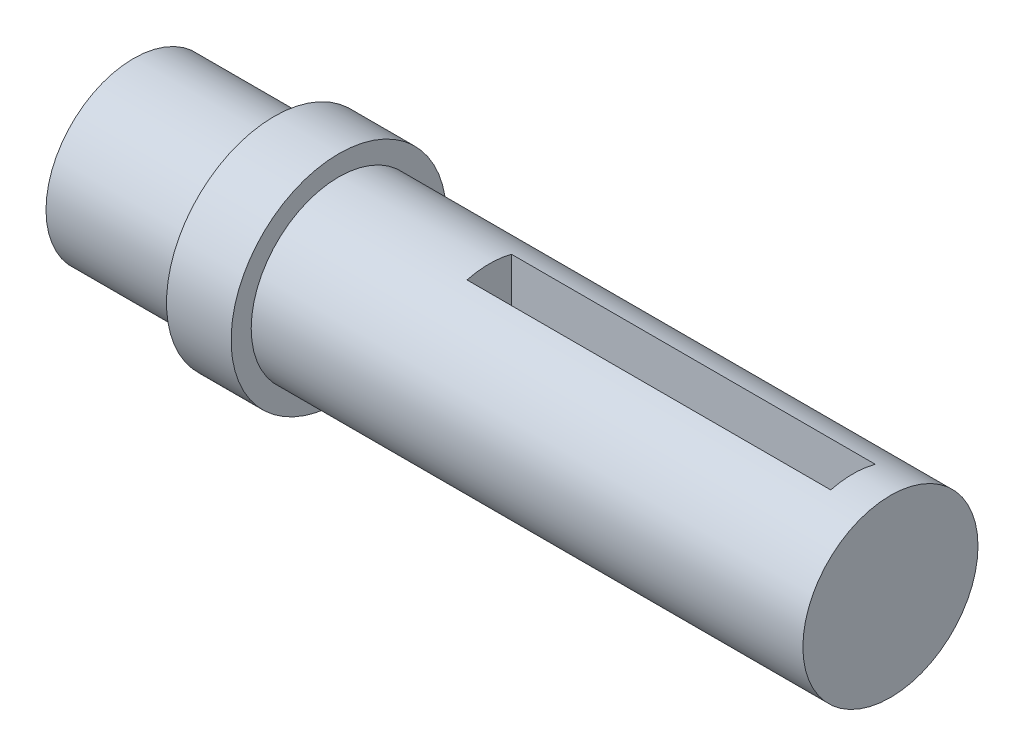
SolidWorks part; units mm, degrees
material "Plain Carbon Steel"
ref_plane "Front Plane" through (0, 0, 0) normal (0, 0, 1) x (1, 0, 0)
ref_plane "Top Plane" through (0, 0, 0) normal (0, 1, 0) x (1, 0, 0)
ref_plane "Right Plane" through (0, 0, 0) normal (1, 0, 0) x (0, 0, -1)
sketch "Sketch1" plane through (0, 0, 0) normal (0, 0, 1) x (1, 0, 0)
  line L0 (0, 0) -> (161.48, 0) construction
  line L1 (161.48, 0) -> (161.48, 18.68)
  line L2 (161.48, 18.68) -> (43.78, 18.68)
  line L3 (43.78, 18.68) -> (43.78, 22.97)
  line L4 (43.78, 22.97) -> (30, 22.97)
  line L5 (30, 22.97) -> (30, 18.68)
  line L6 (30, 18.68) -> (0, 18.68)
  line L7 (0, 18.68) -> (0, 0)
  line L8 (0, 0) -> (161.48, 0)
  dimension "D1" = 16.38
  dimension "D2" = 22.97
  dimension "D3" = 16.38
  dimension "D4" = 117.7
  dimension "D5" = 13.78
  dimension "D6" = 30
revolve "Revolve1" add sketch "Sketch1" angle 360 about L0
sketch "Sketch3" plane through (0, 0, 0) normal (0, 1, 0) x (1, 0, 0)
  line L0 (0, 0) -> (161.48, 0) construction
  line L1 (161.48, -18.68) -> (161.48, 18.68) construction
  line L2 (43.78, -22.97) -> (43.78, 22.97) construction
  line L3 (153.49, -4.745) -> (75.89, -4.745)
  line L4 (153.49, -4.745) -> (153.49, 4.745)
  line L5 (153.49, 4.745) -> (75.89, 4.745)
  line L6 (75.89, -4.745) -> (75.89, 4.745)
  line L7 (153.49, -4.745) -> (75.89, 4.745) construction
  line L8 (153.49, 4.745) -> (75.89, -4.745) construction
  point P5 (114.69, 0)
  dimension "D1" = 32.11
  dimension "D2" = 77.6
  dimension "D3" = 9.49
extrude "Cut-Extrude2" cut sketch "Sketch3" against normal through all both and the other way through all
